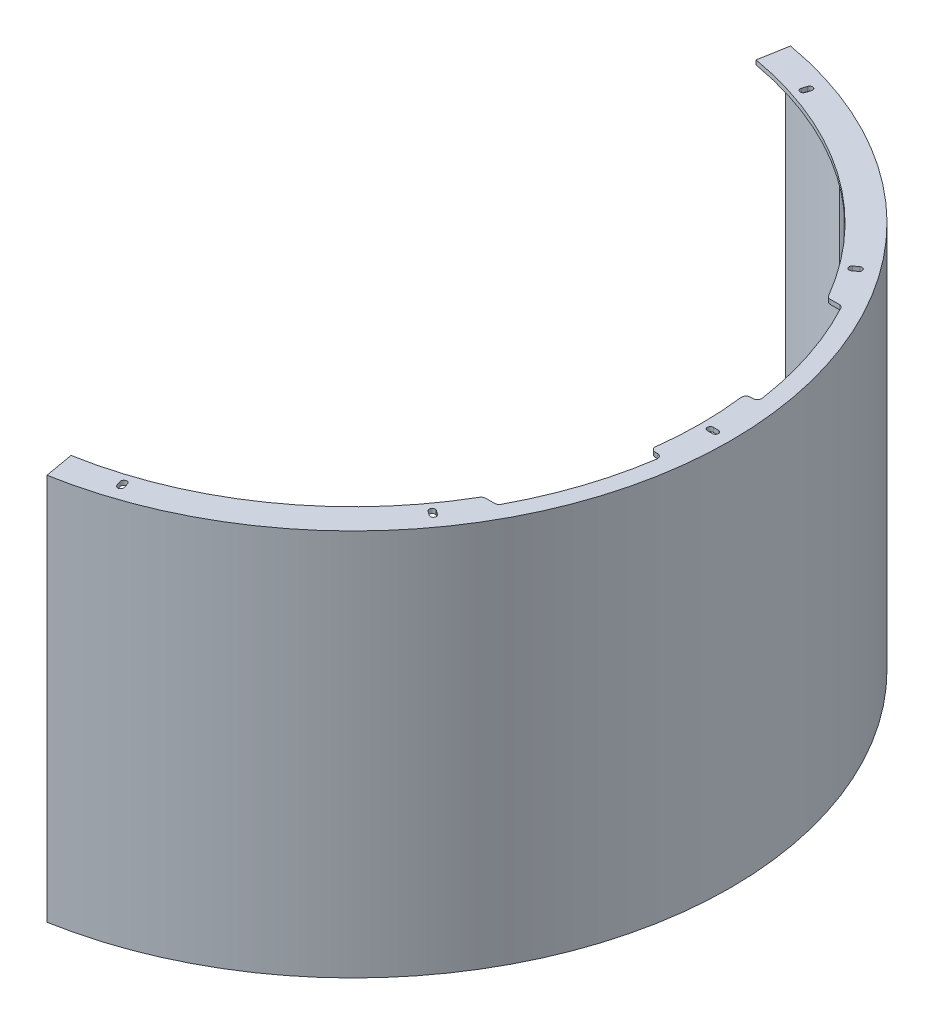
SolidWorks part; units mm, degrees
ref_plane "Front Plane" through (0, 0, 0) normal (0, 0, 1) x (1, 0, 0)
ref_plane "Top Plane" through (0, 0, 0) normal (0, 1, 0) x (1, 0, 0)
ref_plane "Right Plane" through (0, 0, 0) normal (1, 0, 0) x (0, 0, -1)
sketch "Sketch3" plane through (0, 0, 0) normal (0, 1, 0) x (1, 0, 0)
  line L0 (0, -251.5) -> (0, 251.5)
  line L1 (-44.1935, 250.6336) -> (-43.6725, 247.6791)
  line L2 (-43.6725, -247.6791) -> (-44.1935, -250.6336)
  arc A0 (0, 251.5) -> (0, -251.5) centre (0, 0) cw
  arc A1 (0, 251.5) -> (-43.6725, 247.6791) centre (0, 0) ccw
  arc A2 (0, -251.5) -> (-43.6725, -247.6791) centre (0, 0) cw
  arc A3 (0, 254.5) -> (0, -254.5) centre (0, 0) cw
  arc A4 (0, 254.5) -> (-44.1935, 250.6336) centre (0, 0) ccw
  arc A5 (0, -254.5) -> (-44.1935, -250.6336) centre (0, 0) cw
  point P4 (0, 0)
  dimension "D1" = 503
  dimension "D2" = 3
  dimension "D3" = 3
  dimension "D4" = 3
extrude "Boss-Extrude1" add sketch "Sketch3" along normal blind 255 contours A5 A3 A4 L1 A1 A0 A2 L2
sketch "Sketch6" plane through (0, 255, 0) normal (0, 1, 0) x (1, 0, 0)
  line L0 (0, -256) -> (0, 256)
  line L1 (-2, 253.0819) -> (-2, 247.0819)
  line L2 (-1, 246.0819) -> (1, 246.0819)
  line L3 (2, 247.0819) -> (2, 253.0819)
  line L4 (-2, 253.0819) -> (2, 253.0819)
  line L54 (108.0062, 228.8867) -> (105.4029, 223.4809)
  line L55 (105.87, 222.146) -> (107.6719, 221.2783)
  line L56 (109.0068, 221.7454) -> (111.6101, 227.1512)
  line L57 (108.0062, 228.8867) -> (111.6101, 227.1512)
  line L58 (196.6204, 159.3577) -> (191.9294, 155.6167)
  line L59 (191.7711, 154.2114) -> (193.0181, 152.6477)
  line L60 (194.4234, 152.4894) -> (199.1144, 156.2303)
  line L61 (196.6204, 159.3577) -> (199.1144, 156.2303)
  line L62 (246.2916, 58.2659) -> (240.442, 56.9308)
  line L63 (239.6896, 55.7333) -> (240.1347, 53.7835)
  line L64 (241.3321, 53.031) -> (247.1817, 54.3662)
  line L65 (246.2916, 58.2659) -> (247.1817, 54.3662)
  line L66 (247.1817, -54.3662) -> (241.3321, -53.031)
  line L67 (240.1347, -53.7835) -> (239.6896, -55.7333)
  line L68 (240.442, -56.9308) -> (246.2916, -58.2659)
  line L69 (247.1817, -54.3662) -> (246.2916, -58.2659)
  line L70 (199.1144, -156.2303) -> (194.4234, -152.4894)
  line L71 (193.0181, -152.6477) -> (191.7711, -154.2114)
  line L72 (191.9294, -155.6167) -> (196.6204, -159.3577)
  line L73 (199.1144, -156.2303) -> (196.6204, -159.3577)
  line L74 (111.6101, -227.1512) -> (109.0068, -221.7454)
  line L75 (107.6719, -221.2783) -> (105.87, -222.146)
  line L76 (105.4029, -223.4809) -> (108.0062, -228.8867)
  line L77 (111.6101, -227.1512) -> (108.0062, -228.8867)
  line L78 (2, -253.0819) -> (2, -247.0819)
  line L79 (1, -246.0819) -> (-1, -246.0819)
  line L80 (-2, -247.0819) -> (-2, -253.0819)
  line L81 (2, -253.0819) -> (-2, -253.0819)
  arc A2 (2, 247.0819) -> (1, 246.0819) centre (1, 247.0819) cw
  arc A3 (-2, 247.0819) -> (-1, 246.0819) centre (-1, 247.0819) ccw
  arc A26 (109.0068, 221.7454) -> (107.6719, 221.2783) centre (108.1058, 222.1792) cw
  arc A27 (105.4029, 223.4809) -> (105.87, 222.146) centre (106.3039, 223.047) ccw
  arc A28 (194.4234, 152.4894) -> (193.0181, 152.6477) centre (193.7999, 153.2712) cw
  arc A29 (191.9294, 155.6167) -> (191.7711, 154.2114) centre (192.5529, 154.8349) ccw
  arc A30 (241.3321, 53.031) -> (240.1347, 53.7835) centre (241.1096, 54.006) cw
  arc A31 (240.442, 56.9308) -> (239.6896, 55.7333) centre (240.6645, 55.9558) ccw
  arc A32 (240.442, -56.9308) -> (239.6896, -55.7333) centre (240.6645, -55.9558) cw
  arc A33 (241.3321, -53.031) -> (240.1347, -53.7835) centre (241.1096, -54.006) ccw
  arc A34 (191.9294, -155.6167) -> (191.7711, -154.2114) centre (192.5529, -154.8349) cw
  arc A35 (194.4234, -152.4894) -> (193.0181, -152.6477) centre (193.7999, -153.2712) ccw
  arc A36 (105.4029, -223.4809) -> (105.87, -222.146) centre (106.3039, -223.047) cw
  arc A37 (109.0068, -221.7454) -> (107.6719, -221.2783) centre (108.1058, -222.1792) ccw
  arc A38 (-2, -247.0819) -> (-1, -246.0819) centre (-1, -247.0819) cw
  arc A39 (2, -247.0819) -> (1, -246.0819) centre (1, -247.0819) ccw
  point P9 (0, 0)
  point P19 (2, 246.0819)
  point P22 (-2, 246.0819)
  point P23 (0, 246.0819)
  point P59 (0, 0)
  point P68 (0, 0)
  point P76 (0, 0)
  dimension "D3" = 1
  dimension "D1" = 7
  dimension "D2" = 4
  dimension "D4" = 0
  dimension "D5" = 7
  dimension "D6" = 256
  dimension "D7" = 8
extrude "Boss-Extrude2" add sketch "Sketch6" against normal blind 255 separate body
combine bodies "Combine2" operation type add bodies to combine 109 101 115 116 117 118 119 120 121
sketch "Sketch7" plane through (0, 255, 0) normal (0, 1, 0) x (1, 0, 0)
  line L0 (-44.1935, 250.6336) -> (-40.7205, 230.9374)
  line L1 (-44.1935, -250.6336) -> (-40.7205, -230.9374)
  arc A0 (-40.7205, 230.9374) -> (-40.7205, -230.9374) centre (0, 0) cw
  arc A2 (-44.1935, 250.6336) -> (-44.1935, -250.6336) centre (0, 0) cw
  arc A3 (-44.1935, -250.6336) -> (-44.1935, 250.6336) centre (0, 0) ccw construction
extrude "Boss-Extrude3" add sketch "Sketch7" along normal blind 3 contours A2 L0 A0 L1
sketch "Sketch8" plane through (0, 255, 0) normal (0, -1, 0) x (1, 0, 0)
  line L0 (240.8, 0) -> (244.2, 0) construction
  line L1 (240.8, 2) -> (244.2, 2)
  line L2 (240.8, -2) -> (244.2, -2)
  line L3 (194.8113, -141.5387) -> (197.562, -143.5372) construction
  line L12 (195.9869, -139.9207) -> (198.7375, -141.9191)
  line L21 (193.6357, -143.1567) -> (196.3864, -145.1552)
  line L24 (74.4113, -229.0144) -> (75.462, -232.248) construction
  line L27 (76.3134, -228.3964) -> (77.3641, -231.63)
  line L28 (72.5092, -229.6324) -> (73.5598, -232.866)
  line L29 (-74.4113, -229.0144) -> (-75.462, -232.248) construction
  line L30 (-72.5092, -229.6324) -> (-73.5598, -232.866)
  line L31 (-76.3134, -228.3964) -> (-77.3641, -231.63)
  line L32 (-194.8113, -141.5387) -> (-197.562, -143.5372) construction
  line L33 (-193.6357, -143.1567) -> (-196.3864, -145.1552)
  line L34 (-195.9869, -139.9207) -> (-198.7375, -141.9191)
  line L35 (-240.8, 0) -> (-244.2, 0) construction
  line L36 (-240.8, -2) -> (-244.2, -2)
  line L37 (-240.8, 2) -> (-244.2, 2)
  line L38 (-194.8113, 141.5387) -> (-197.562, 143.5372) construction
  line L39 (-195.9869, 139.9207) -> (-198.7375, 141.9191)
  line L40 (-193.6357, 143.1567) -> (-196.3864, 145.1552)
  line L41 (-74.4113, 229.0144) -> (-75.462, 232.248) construction
  line L42 (-76.3134, 228.3964) -> (-77.3641, 231.63)
  line L43 (-72.5092, 229.6324) -> (-73.5598, 232.866)
  line L44 (74.4113, 229.0144) -> (75.462, 232.248) construction
  line L45 (72.5092, 229.6324) -> (73.5598, 232.866)
  line L46 (76.3134, 228.3964) -> (77.3641, 231.63)
  line L47 (194.8113, 141.5387) -> (197.562, 143.5372) construction
  line L48 (193.6357, 143.1567) -> (196.3864, 145.1552)
  line L49 (195.9869, 139.9207) -> (198.7375, 141.9191)
  circle A1 centre (242.5, 0) radius 1.7 construction
  arc A2 (240.8, 2) -> (240.8, -2) centre (240.8, 0) ccw
  arc A3 (244.2, -2) -> (244.2, 2) centre (244.2, 0) ccw
  arc A24 (195.9869, -139.9207) -> (193.6357, -143.1567) centre (194.8113, -141.5387) ccw
  arc A25 (196.3864, -145.1552) -> (198.7375, -141.9191) centre (197.562, -143.5372) ccw
  arc A26 (76.3134, -228.3964) -> (72.5092, -229.6324) centre (74.4113, -229.0144) ccw
  arc A27 (73.5598, -232.866) -> (77.3641, -231.63) centre (75.462, -232.248) ccw
  arc A28 (-72.5092, -229.6324) -> (-76.3134, -228.3964) centre (-74.4113, -229.0144) ccw
  arc A29 (-77.3641, -231.63) -> (-73.5598, -232.866) centre (-75.462, -232.248) ccw
  arc A30 (-193.6357, -143.1567) -> (-195.9869, -139.9207) centre (-194.8113, -141.5387) ccw
  arc A31 (-198.7375, -141.9191) -> (-196.3864, -145.1552) centre (-197.562, -143.5372) ccw
  arc A32 (-240.8, -2) -> (-240.8, 2) centre (-240.8, 0) ccw
  arc A33 (-244.2, 2) -> (-244.2, -2) centre (-244.2, 0) ccw
  arc A34 (-195.9869, 139.9207) -> (-193.6357, 143.1567) centre (-194.8113, 141.5387) ccw
  arc A35 (-196.3864, 145.1552) -> (-198.7375, 141.9191) centre (-197.562, 143.5372) ccw
  arc A36 (-76.3134, 228.3964) -> (-72.5092, 229.6324) centre (-74.4113, 229.0144) ccw
  arc A37 (-73.5598, 232.866) -> (-77.3641, 231.63) centre (-75.462, 232.248) ccw
  arc A38 (72.5092, 229.6324) -> (76.3134, 228.3964) centre (74.4113, 229.0144) ccw
  arc A39 (77.3641, 231.63) -> (73.5598, 232.866) centre (75.462, 232.248) ccw
  arc A40 (193.6357, 143.1567) -> (195.9869, 139.9207) centre (194.8113, 141.5387) ccw
  arc A41 (198.7375, 141.9191) -> (196.3864, 145.1552) centre (197.562, 143.5372) ccw
  point P6 (242.5, 0)
  point P16 (196.1866, -142.5379)
  point P23 (74.9366, -230.6312)
  point P28 (0, 0)
  point P31 (-74.9366, -230.6312)
  point P35 (0, 0)
  point P39 (-196.1866, -142.5379)
  point P44 (0, 0)
  point P47 (-242.5, 0)
  point P54 (-196.1866, 142.5379)
  point P57 (0, 0)
  point P62 (-74.9366, 230.6312)
  point P69 (74.9366, 230.6312)
  point P76 (196.1866, 142.5379)
  point P81 (0, 0)
  dimension "D1" = 2
extrude "Cut-Extrude3" cut sketch "Sketch8" against normal blind 5
pattern_linear "LPattern1" count 2 spacing 258 along (0, -1, 0) of "Boss-Extrude3"
pattern_linear "LPattern2" count 2 spacing 258 along (0, -1, 0) of "Cut-Extrude3"
sketch "Sketch11" plane through (0, 258, 0) normal (0, 1, 0) x (1, 0, 0)
  line L0 (-44.1935, 250.6336) -> (0, 0)
  line L1 (0, 0) -> (44.1935, 250.6336)
  line L2 (-117.5787, 0) -> (117.5787, 0) construction
  arc A0 (-44.1935, 250.6336) -> (44.1935, 250.6336) centre (0, 0) cw
extrude "Cut-Extrude7" cut sketch "Sketch11" against normal blind 324
mirror "Mirror1" about plane through (0, 0, 0) normal (0, 0, 1) of "Cut-Extrude7"
sketch "Sketch13" plane through (0, 258, 0) normal (0, 1, 0) x (1, 0, 0)
  line L3 (240.8, 32.1355) -> (189.8429, 32.1355)
  line L4 (189.8429, 32.1355) -> (189.8429, 116.171)
  line L5 (189.8429, 116.171) -> (213.358, 116.171)
  line L6 (-117.5787, 0) -> (117.5787, 0) construction
  line L7 (189.8429, -116.171) -> (213.358, -116.171)
  line L8 (189.8429, -32.1355) -> (189.8429, -116.171)
  line L9 (240.8, -32.1355) -> (189.8429, -32.1355)
  arc A0 (240.8, 32.1355) -> (213.358, 116.171) centre (0, 0) ccw
  arc A1 (240.8, -32.1355) -> (213.358, -116.171) centre (0, 0) cw
extrude "Cut-Extrude10" cut sketch "Sketch13" against normal blind 5
fillet "Fillet2" radius 3 8 edges at (203.7021, 256.5, 116.171) (213.358, 256.5, 116.171) (232.2877, 256.5, 32.1355) (240.8, 256.5, 32.1355) (232.2877, 256.5, -32.1355) (240.8, 256.5, -32.1355) (213.358, 256.5, -116.171) (203.7021, 256.5, -116.171)
